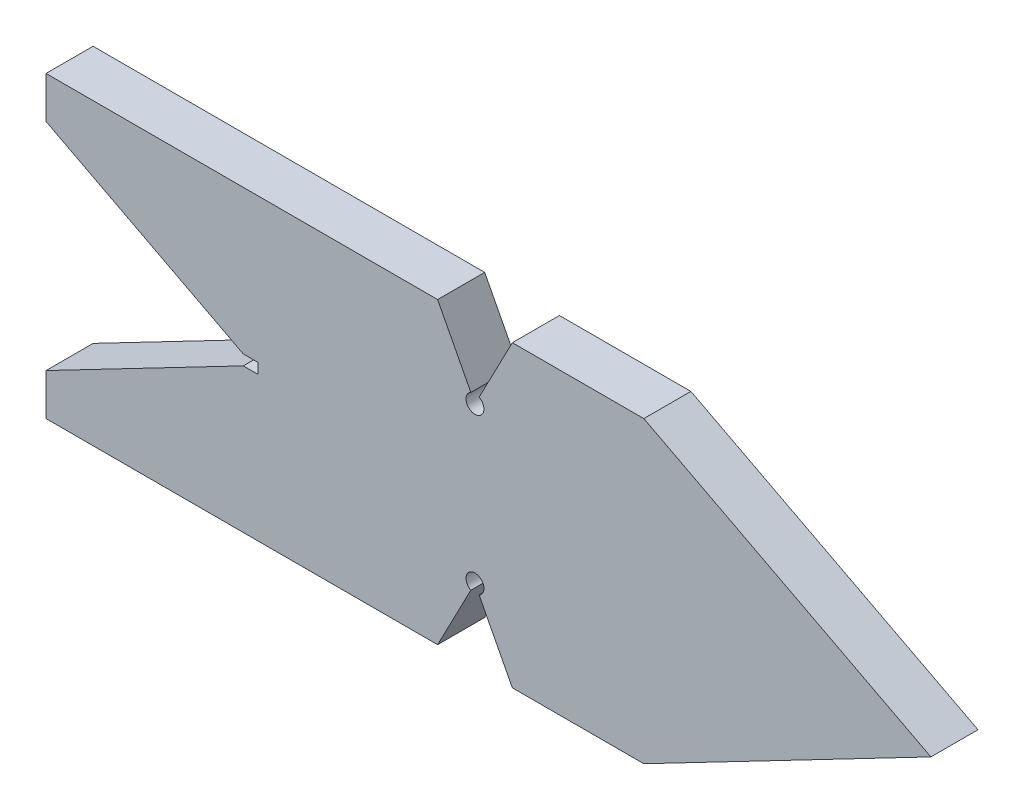
SolidWorks part; units mm, degrees
ref_plane "Front Plane" through (0, 0, 0) normal (0, 0, 1) x (1, 0, 0)
ref_plane "Top Plane" through (0, 0, 0) normal (0, 1, 0) x (1, 0, 0)
ref_plane "Right Plane" through (0, 0, 0) normal (1, 0, 0) x (0, 0, -1)
ref_plane "Plane1" through (0, 0, 0) normal (0, 0, -1) x (-1, 0, 0)
sketch "Sketch1" plane through (0, 0, 0) normal (0, 0, -1) x (-1, 0, 0)
  line L0 (-33.2777, 0) -> (0, 0)
  line L1 (0, 0) -> (0, 3.5346)
  line L2 (0, 3.5346) -> (-16.7615, 12.2601)
  line L3 (-16.7615, 12.2601) -> (-18.0315, 12.2601)
  line L4 (-18.0315, 12.2601) -> (-18.0315, 13.1399)
  line L5 (-18.0315, 13.1399) -> (-16.7615, 13.1399)
  line L6 (-16.7615, 13.1399) -> (0, 21.8654)
  line L7 (0, 21.8654) -> (0, 25.4)
  line L8 (0, 25.4) -> (-33.2777, 25.4)
  line L9 (-33.2777, 25.4) -> (-36.1008, 19.9768)
  line L10 (-36.8045, 19.9768) -> (-39.6277, 25.4)
  line L11 (-39.6277, 25.4) -> (-50.8, 25.4)
  line L12 (-50.8, 25.4) -> (-75.1965, 12.7)
  line L13 (-75.1965, 12.7) -> (-50.8, 0)
  line L14 (-50.8, 0) -> (-39.6277, 0)
  line L15 (-39.6277, 0) -> (-36.8045, 5.4232)
  line L16 (-36.1008, 5.4232) -> (-33.2777, 0)
  line L17 (-18.0315, 12.7) -> (-75.1965, 12.7) construction
  arc A0 (-36.1008, 19.9768) -> (-36.8045, 19.9768) centre (-36.4527, 19.3009) cw
  arc A1 (-36.8045, 5.4232) -> (-36.1008, 5.4232) centre (-36.4527, 6.0991) cw
  dimension "D12" = 0.762
  dimension "D1" = 25.4
  dimension "D2" = 55
  dimension "D3" = 55
  dimension "D4" = 55
  dimension "D5" = 55
  dimension "D6" = 50.8
  dimension "D7" = 3.5346
  dimension "D8" = 0.8799
  dimension "D9" = 6.35
  dimension "D10" = 11.1723
  dimension "D11" = 1.27
extrude "Boss-Extrude1" add sketch "Sketch1" against normal blind 4
sketch "Sketch2" plane through (0, 0, 0) normal (0, 0, -1) x (-1, 0, 0)
  text T0 "55"
  point P1 (-41.266, 10.2738)
  point P2 (-39.7653, 11.663)
  point P3 (0, 0)
extrude "Cut-Extrude1" cut sketch "Sketch2" against normal blind 1
